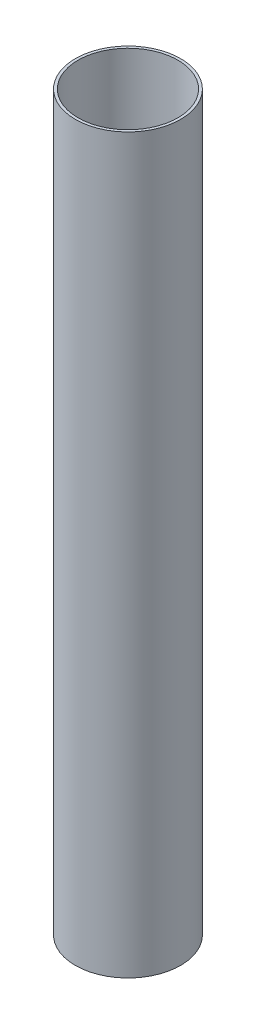
SolidWorks part; units mm, degrees
material "Corrugated Paper"
ref_plane "Front Plane" through (0, 0, 0) normal (0, 0, 1) x (1, 0, 0)
ref_plane "Top Plane" through (0, 0, 0) normal (0, 1, 0) x (1, 0, 0)
ref_plane "Right Plane" through (0, 0, 0) normal (1, 0, 0) x (0, 0, -1)
sketch "Sketch1" plane through (0, 0, 0) normal (0, 1, 0) x (1, 0, 0)
  circle A0 centre (0, 0) radius 40.1574
  circle A1 centre (0, 0) radius 38.1
  dimension "D1" = 76.2
  dimension "D2" = 80.3148
extrude "Boss-Extrude1" add sketch "Sketch1" against normal blind 558.8
